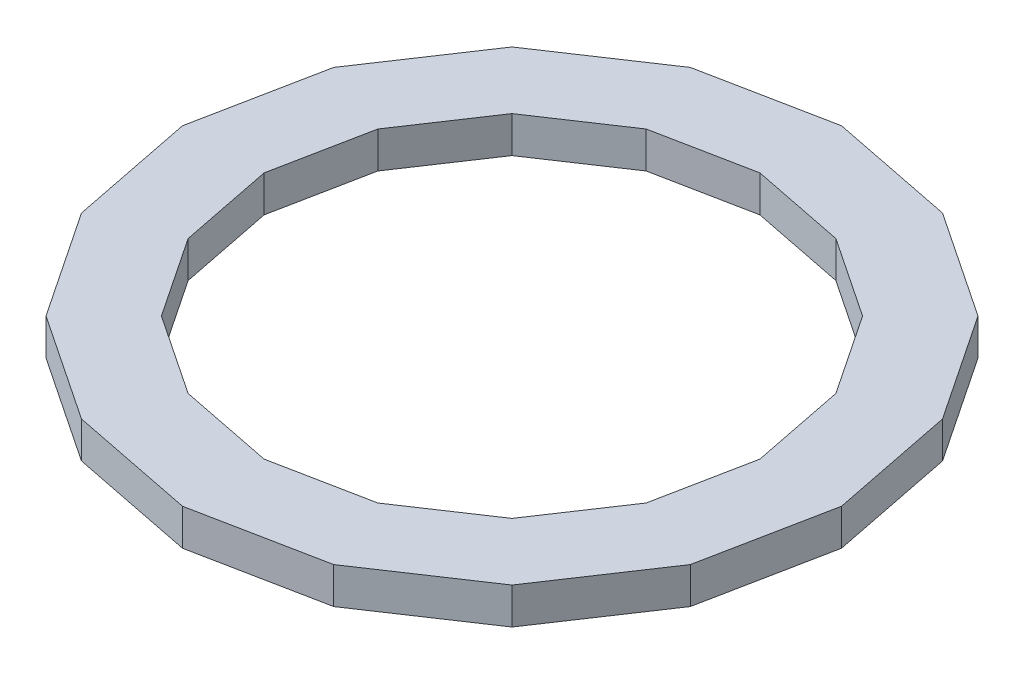
SolidWorks part; units mm, degrees
ref_plane "Front Plane" through (0, 0, 0) normal (0, 0, 1) x (1, 0, 0)
ref_plane "Top Plane" through (0, 0, 0) normal (0, 1, 0) x (1, 0, 0)
ref_plane "Right Plane" through (0, 0, 0) normal (1, 0, 0) x (0, 0, -1)
sketch "Sketch1" plane through (0, 0, 0) normal (0, 1, 0) x (1, 0, 0)
  line L1 (129.7788, 0) -> (119.9, 49.6642)
  line L2 (119.9, 49.6642) -> (91.7675, 91.7675)
  line L3 (91.7675, 91.7675) -> (49.6642, 119.9)
  line L4 (49.6642, 119.9) -> (0, 129.7788)
  line L5 (0, 129.7788) -> (-49.6642, 119.9)
  line L6 (-49.6642, 119.9) -> (-91.7675, 91.7675)
  line L7 (-91.7675, 91.7675) -> (-119.9, 49.6642)
  line L8 (-119.9, 49.6642) -> (-129.7788, 0)
  line L9 (-129.7788, 0) -> (-119.9, -49.6642)
  line L10 (-119.9, -49.6642) -> (-91.7675, -91.7675)
  line L11 (-91.7675, -91.7675) -> (-49.6642, -119.9)
  line L12 (-49.6642, -119.9) -> (0, -129.7788)
  line L13 (0, -129.7788) -> (49.6642, -119.9)
  line L14 (49.6642, -119.9) -> (91.7675, -91.7675)
  line L15 (91.7675, -91.7675) -> (119.9, -49.6642)
  line L16 (119.9, -49.6642) -> (129.7788, 0)
  line L17 (172.5098, 0) -> (159.3783, 66.0167)
  line L18 (159.3783, 66.0167) -> (121.9829, 121.9829)
  line L19 (121.9829, 121.9829) -> (66.0167, 159.3783)
  line L20 (66.0167, 159.3783) -> (0, 172.5098)
  line L21 (0, 172.5098) -> (-66.0167, 159.3783)
  line L22 (-66.0167, 159.3783) -> (-121.9829, 121.9829)
  line L23 (-121.9829, 121.9829) -> (-159.3783, 66.0167)
  line L24 (-159.3783, 66.0167) -> (-172.5098, 0)
  line L25 (-172.5098, 0) -> (-159.3783, -66.0167)
  line L26 (-159.3783, -66.0167) -> (-121.9829, -121.9829)
  line L27 (-121.9829, -121.9829) -> (-66.0167, -159.3783)
  line L28 (-66.0167, -159.3783) -> (0, -172.5098)
  line L29 (0, -172.5098) -> (66.0167, -159.3783)
  line L30 (66.0167, -159.3783) -> (121.9829, -121.9829)
  line L31 (121.9829, -121.9829) -> (159.3783, -66.0167)
  line L32 (159.3783, -66.0167) -> (172.5098, 0)
  circle A1 centre (0, 0) radius 127.2851 construction
  circle A2 centre (0, 0) radius 169.1951 construction
  dimension "D1" = 41.91
  dimension "D2" = 67.31
extrude "Boss-Extrude1" add sketch "Sketch1" along normal blind 19.05
